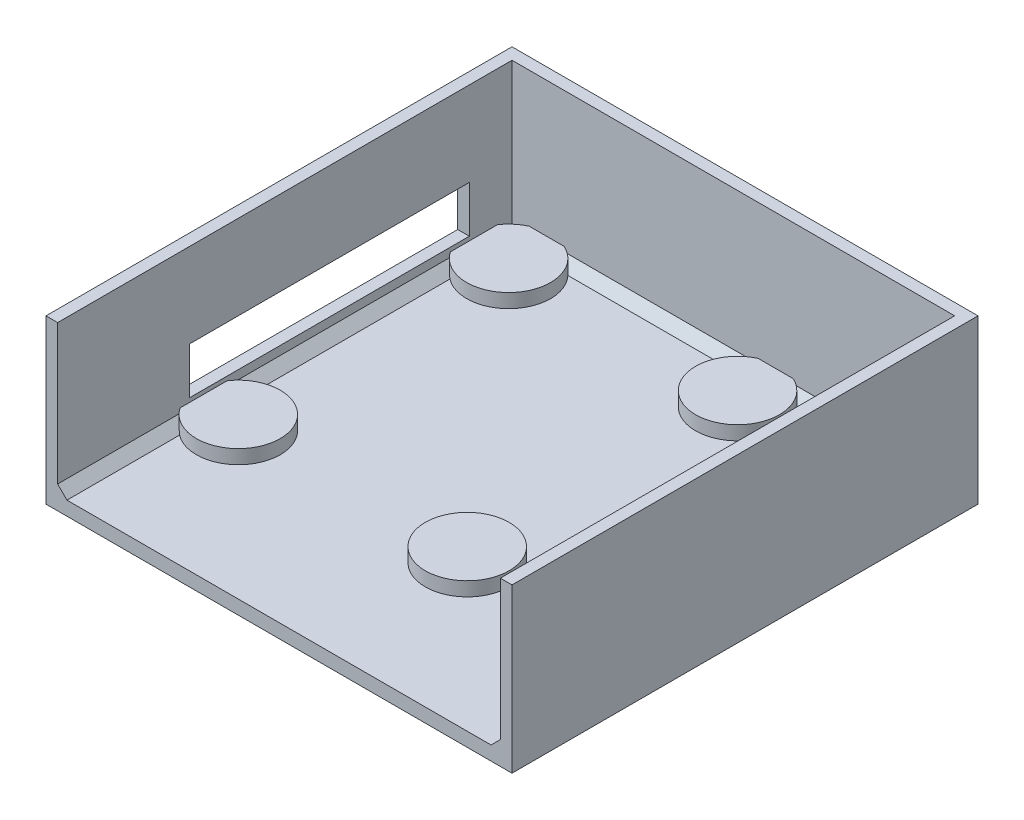
SolidWorks part; units mm, degrees
ref_plane "Спереди" through (0, 0, 0) normal (0, 0, 1) x (1, 0, 0)
ref_plane "Сверху" through (0, 0, 0) normal (0, 1, 0) x (1, 0, 0)
ref_plane "Справа" through (0, 0, 0) normal (1, 0, 0) x (0, 0, -1)
sketch "Эскиз1" plane through (0, 0, 0) normal (0, 1, 0) x (1, 0, 0)
  line L1 (-69.9136, 36.3319) -> (30.0864, 36.3319)
  line L2 (-69.9136, 36.3319) -> (-69.9136, -63.6681)
  line L3 (-69.9136, -63.6681) -> (30.0864, -63.6681)
  line L4 (30.0864, 36.3319) -> (30.0864, -63.6681)
  dimension "D1" = 100
  dimension "D2" = 100
extrude "Бобышка-Вытянуть1" add sketch "Эскиз1" along normal blind 3
sketch "Эскиз2" plane through (0, 3, 0) normal (0, 1, 0) x (1, 0, 0)
  line L0 (27.5864, -61.0418) -> (27.5864, -63.6681)
  line L1 (-69.9136, 36.3319) -> (30.0864, 36.3319)
  line L2 (-69.9136, 36.3319) -> (-69.9136, -63.6681)
  line L3 (-69.9136, -63.6681) -> (-67.4136, -63.6681)
  line L4 (30.0864, 36.3319) -> (30.0864, -63.6681)
  line L5 (-67.4136, 33.8319) -> (27.5864, 33.8319)
  line L6 (-67.4136, 33.8319) -> (-67.4136, -61.0418)
  line L8 (27.5864, 33.8319) -> (27.5864, -61.0418)
  line L9 (-67.4136, -61.0418) -> (-67.4136, -63.6681)
  line L10 (27.5864, -63.6681) -> (30.0864, -63.6681)
  dimension "D1" = 2.5
  dimension "D2" = 2.5
  dimension "D3" = 2.5
extrude "Бобышка-Вытянуть2" add sketch "Эскиз2" along normal blind 32
sketch "Эскиз3" plane through (0, 3, 0) normal (0, 1, 0) x (1, 0, 0)
  circle A0 centre (-10.8393, 25.6579) radius 9
  circle A1 centre (-59.9626, 25.6579) radius 9
  circle A2 centre (-59.9626, -32.3485) radius 9
  circle A3 centre (-10.8393, -32.3485) radius 9
  dimension "D1" = 18
  dimension "D2" = 18
  dimension "D3" = 18
  dimension "D4" = 18
  dimension "D5" = 49.1233
  dimension "D6" = 58.0065
  dimension "D7" = 58.0065
  dimension "D8" = 49.1233
  dimension "D9" = 76.0121
extrude "Бобышка-Вытянуть3" add sketch "Эскиз3" along normal blind 3
sketch "Эскиз4" plane through (-69.9136, 0, 0) normal (-1, 0, 0) x (0, 0, 1)
  line L1 (-24.6734, 16.8739) -> (35.3266, 16.8739)
  line L2 (-24.6734, 16.8739) -> (-24.6734, 6.8739)
  line L3 (-24.6734, 6.8739) -> (35.3266, 6.8739)
  line L4 (35.3266, 16.8739) -> (35.3266, 6.8739)
  line L5 (-36.3319, 35) -> (-36.3319, 0) construction
  line L6 (-36.3319, 0) -> (63.6681, 0) construction
  dimension "D1" = 60
  dimension "D2" = 10
  dimension "D3" = 11.6585
  dimension "D4" = 6.8739
extrude "Вырез-Вытянуть1" cut sketch "Эскиз4" against normal up to surface (2.5 mm away) up to face at (-67.4136, 9.3333, 7.2029)
chamfer "Фаска1" distance 2 angle 45 5 edges at (-67.4136, 3, 50.5323) (10.2568, 3, -33.8319) (27.5864, 3, 14.9181) (-67.4136, 3, 3.3453) (-35.401, 3, -33.8319)
